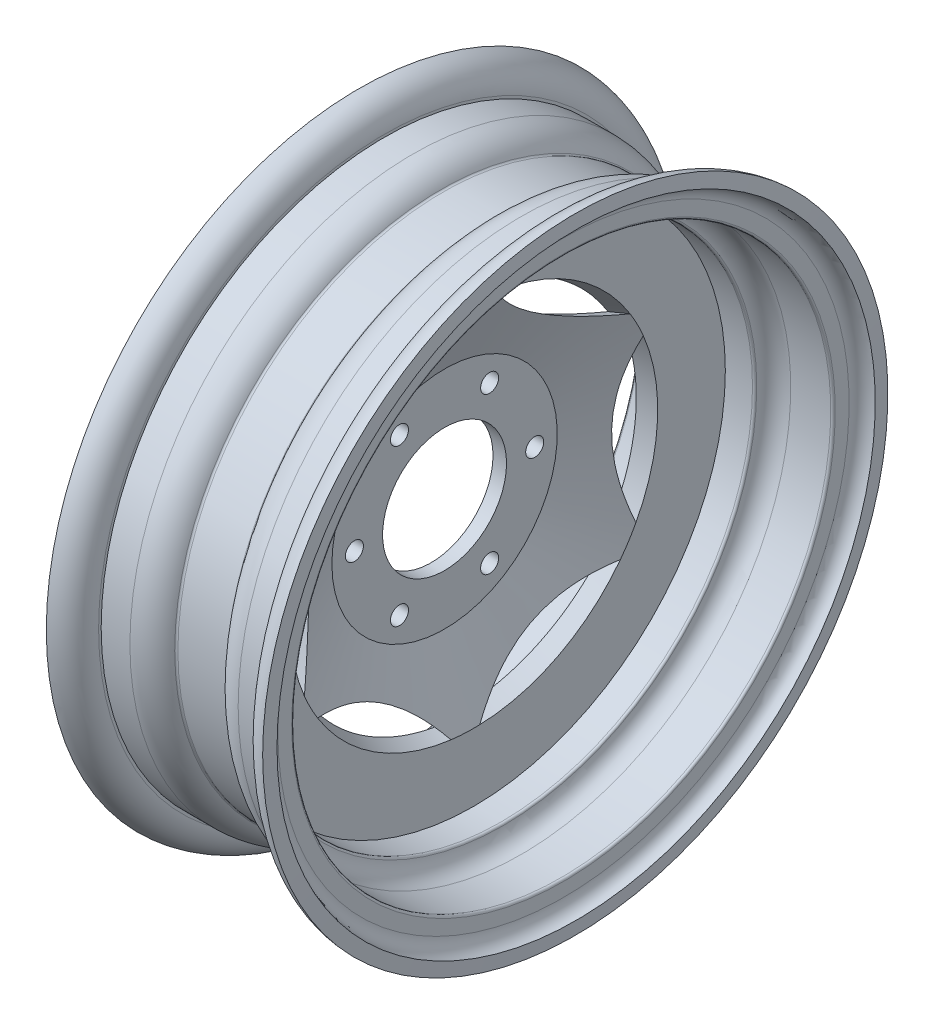
SolidWorks part; units mm, degrees
ref_plane "Front Plane" through (0, 0, 0) normal (0, 0, 1) x (1, 0, 0)
ref_plane "Top Plane" through (0, 0, 0) normal (0, 1, 0) x (1, 0, 0)
ref_plane "Right Plane" through (0, 0, 0) normal (1, 0, 0) x (0, 0, -1)
sketch "Sketch1" plane through (0, 0, 0) normal (0, 0, 1) x (1, 0, 0)
  line L0 (0, 0) -> (0, 50000) construction
  line L1 (0, 0) -> (50000, 0) construction
  line L2 (-15.0556, 111.585) -> (-3, 111.585)
  line L3 (24.0152, 119.6002) -> (41.7678, 119.6002)
  line L4 (-24.0152, 119.6002) -> (-41.7678, 119.6002)
  line L5 (42.7678, 120.6002) -> (42.7678, 126.7434)
  line L6 (-42.7678, 120.6002) -> (-42.7678, 126.7434)
  line L7 (36.7678, 125.6002) -> (36.7678, 126.7434)
  line L8 (24.0152, 125.6002) -> (36.7678, 125.6002)
  line L9 (-10.7315, 117.585) -> (10.7315, 117.585)
  line L10 (-24.0152, 125.6002) -> (-36.7678, 125.6002)
  line L11 (-36.7678, 125.6002) -> (-36.7678, 126.7434)
  line L12 (3, 111.585) -> (3, 81.585)
  line L13 (-3, 111.585) -> (-3, 81.585)
  line L14 (3, 111.585) -> (15.0556, 111.585)
  line L15 (-16, 111.585) -> (16, 111.585) construction
  line L16 (3, 81.585) -> (-10, 50)
  line L17 (-3, 81.585) -> (-16, 50)
  line L18 (-16, 50) -> (-16, 0)
  line L19 (-10, 50) -> (-10, 0)
  line L20 (-10, 0) -> (-16, 0)
  line L21 (48, 138.7189) -> (48.3839, 132.7311)
  line L22 (-48, 138.7189) -> (-48.3839, 132.7311)
  line L23 (24.0152, 119.6002) -> (42.7678, 119.6002) construction
  line L24 (42.7678, 119.6002) -> (42.7678, 126.7434) construction
  line L25 (-24.0152, 119.6002) -> (-42.7678, 119.6002) construction
  line L26 (-42.7678, 119.6002) -> (-42.7678, 126.7434) construction
  line L27 (-11.3493, 117.585) -> (11.3493, 117.585) construction
  arc A0 (16.0495, 112.4741) -> (24.0152, 119.6002) centre (24.0152, 111.585) cw
  arc A1 (-16.0495, 112.4741) -> (-24.0152, 119.6002) centre (-24.0152, 111.585) ccw
  arc A2 (42.7678, 126.7434) -> (48.3839, 132.7311) centre (48.7678, 126.7434) cw
  arc A3 (-42.7678, 126.7434) -> (-48.3839, 132.7311) centre (-48.7678, 126.7434) ccw
  arc A4 (36.7678, 126.7434) -> (48, 138.7189) centre (48.7678, 126.7434) cw
  arc A5 (11.6162, 118.1188) -> (24.0152, 125.6002) centre (24.0152, 111.585) cw
  arc A6 (-11.6162, 118.1188) -> (-24.0152, 125.6002) centre (-24.0152, 111.585) ccw
  arc A7 (-36.7678, 126.7434) -> (-48, 138.7189) centre (-48.7678, 126.7434) ccw
  arc A8 (41.7678, 119.6002) -> (42.7678, 120.6002) centre (41.7678, 120.6002) ccw
  arc A9 (-41.7678, 119.6002) -> (-42.7678, 120.6002) centre (-41.7678, 120.6002) cw
  arc A10 (-11.3493, 117.585) -> (-24.0152, 125.6002) centre (-24.0152, 111.585) ccw construction
  arc A11 (-10.7315, 117.585) -> (-11.6162, 118.1188) centre (-10.7315, 118.585) cw
  arc A12 (11.3493, 117.585) -> (24.0152, 125.6002) centre (24.0152, 111.585) cw construction
  arc A13 (11.6162, 118.1188) -> (10.7315, 117.585) centre (10.7315, 118.585) cw
  arc A14 (16, 111.585) -> (24.0152, 119.6002) centre (24.0152, 111.585) cw construction
  arc A15 (15.0556, 111.585) -> (16.0495, 112.4741) centre (15.0556, 112.585) ccw
  arc A16 (-16, 111.585) -> (-24.0152, 119.6002) centre (-24.0152, 111.585) ccw construction
  arc A17 (-16.0495, 112.4741) -> (-15.0556, 111.585) centre (-15.0556, 112.585) ccw
  point P8 (0, 92.9427)
  point P34 (-40.0152, 134.9528)
  point P35 (-16.7746, 123.585)
  point P40 (0, 0)
  point P48 (42.7678, 119.6002)
  point P52 (-42.7678, 119.6002)
  dimension "D4" = 6
  dimension "D5" = 12
  dimension "D10" = 1
  dimension "D2" = 48
  dimension "D3" = 16
  dimension "D6" = 6
  dimension "D7" = 30
  dimension "D8" = 50
  dimension "D9" = 13
  dimension "D11" = 92.9427
  dimension "D12" = 126.7434
  dimension "D1" = 6
revolve "Revolve1" add sketch "Sketch1" angle 360 about L1
sketch "Sketch2" plane through (-10, 0, 0) normal (1, 0, 0) x (0, 0, -1)
  line L0 (0, 0) -> (20, 34.641) construction
  line L1 (0, 0) -> (50000, 0) construction
  circle A0 centre (0, 0) radius 27.5
  circle A1 centre (0, 0) radius 40 construction
  circle A2 centre (20, 34.641) radius 4
  circle A3 centre (40, 0) radius 4
  circle A4 centre (20, -34.641) radius 4
  circle A5 centre (-20, -34.641) radius 4
  circle A6 centre (-40, 0) radius 4
  circle A7 centre (-20, 34.641) radius 4
  point P10 (0, 0)
  point P21 (0, 0)
  dimension "D1" = 80
  dimension "D2" = 55
  dimension "D3" = 60
  dimension "D4" = 8
  dimension "D5" = 6
extrude "Cut-Extrude1" cut sketch "Sketch2" against normal through all
ref_plane "Plane1" through (-26.1495, -10.7628, 0) normal (0.9247, 0.3806, 0) x (0, 0, -1)
sketch "Sketch3" plane through (-26.1495, -10.7628, 0) normal (0.9247, 0.3806, 0) x (0, 0, -1)
  arc A0 (-2.5827, 74.2649) -> (-65.0253, 44.4227) centre (-96.7396, 191.0316) cw
  ellipse E0 centre (0, 3.8061) end of major axis (50, 3.8061) minor radius 46.2368 construction
  ellipse E1 centre (0, -1.1418) end of major axis (81.585, -1.1418) minor radius 75.4445 construction
  ellipse E2 centre (0, 3.8061) end of major axis (50, 3.8061) minor radius 46.2368
  ellipse E3 centre (0, -1.1418) end of major axis (81.585, -1.1418) minor radius 75.4445
  point P25 (0, 0)
  point P26 (0, 0)
  point P27 (0, 0)
  point P28 (-65.0253, 44.4227)
  point P30 (0, 0)
  point P31 (0, 0)
  dimension "D1" = 150
  dimension "D2" = 2.5827
extrude "Cut-Extrude3" cut sketch "Sketch3" along normal through all contours A0 E3
pattern_circular "CirPattern1" count 6 over 360 about axis through (-10, 0, 0) along (1, 0, 0) of "Cut-Extrude3"
